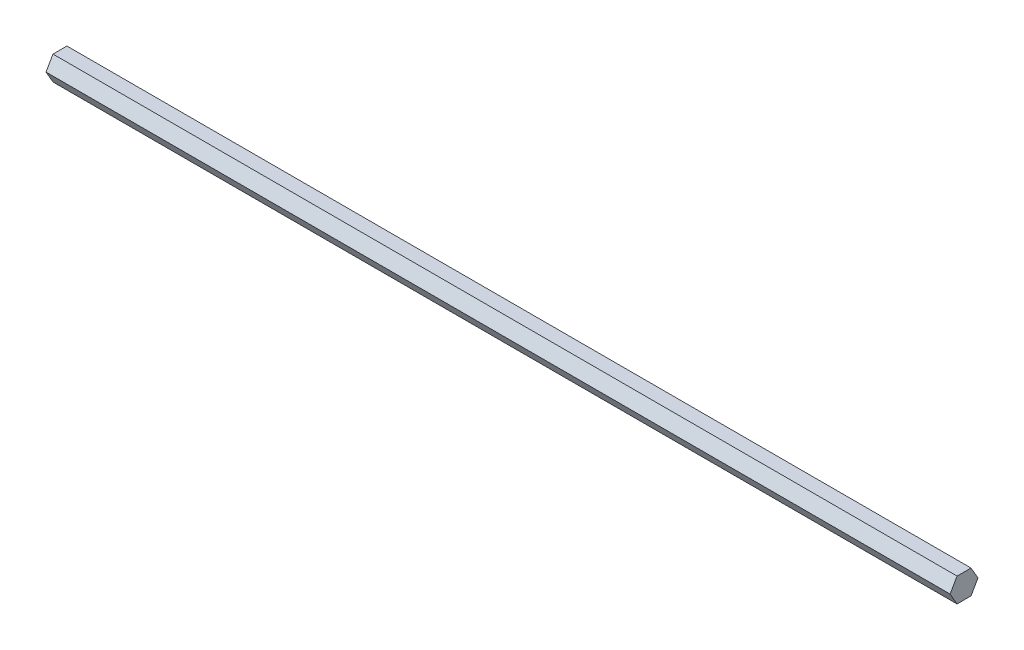
SolidWorks part; units mm, degrees
ref_plane "Alzado" through (0, 0, 0) normal (0, 0, 1) x (1, 0, 0)
ref_plane "Planta" through (0, 0, 0) normal (0, 1, 0) x (1, 0, 0)
ref_plane "Vista lateral" through (0, 0, 0) normal (1, 0, 0) x (0, 0, -1)
sketch "Croquis1" plane through (0, 0, 0) normal (1, 0, 0) x (0, 0, -1)
  line L1 (7.3323, 0) -> (3.6662, 6.35)
  line L2 (3.6662, 6.35) -> (-3.6662, 6.35)
  line L3 (-3.6662, 6.35) -> (-7.3323, 0)
  line L4 (-7.3323, 0) -> (-3.6662, -6.35)
  line L5 (-3.6662, -6.35) -> (3.6662, -6.35)
  line L6 (3.6662, -6.35) -> (7.3323, 0)
  circle A0 centre (0, 0) radius 6.35 construction
  dimension "D1" = 12.7
extrude "Saliente-Extruir1" add sketch "Croquis1" along normal blind 475
